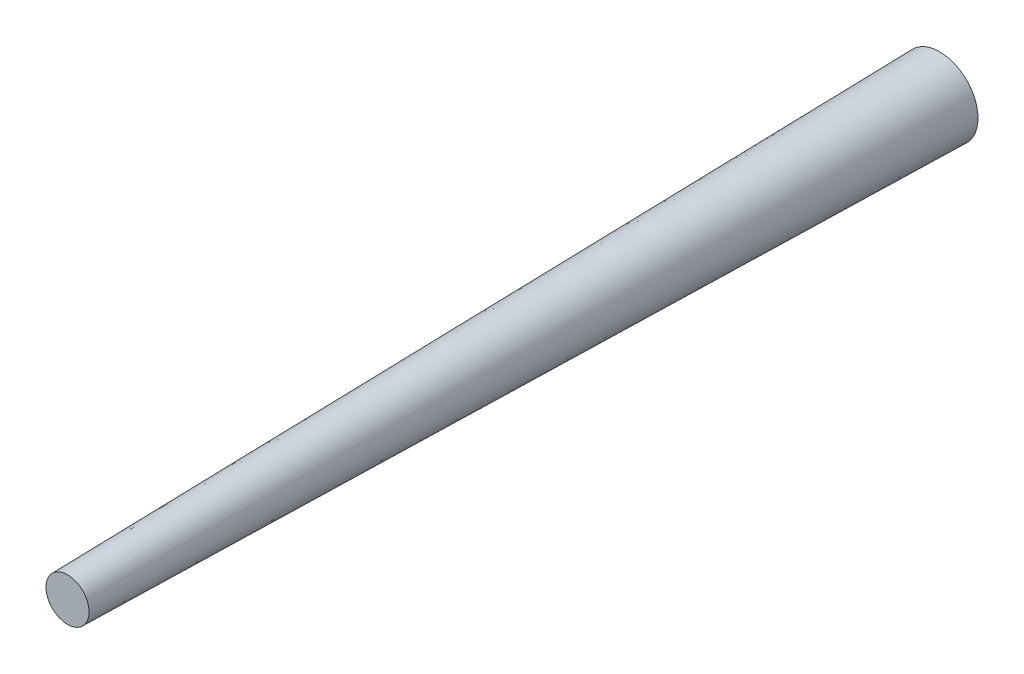
SolidWorks part; units mm, degrees
ref_plane "Front Plane" through (0, 0, 0) normal (0, 0, 1) x (1, 0, 0)
ref_plane "Top Plane" through (0, 0, 0) normal (0, 1, 0) x (1, 0, 0)
ref_plane "Right Plane" through (0, 0, 0) normal (1, 0, 0) x (0, 0, -1)
sketch "Sketch1" plane through (0, 0, 0) normal (0, 1, 0) x (1, 0, 0)
  line L0 (27, -409.6923) -> (0, -409.6923)
  line L1 (0, -409.6923) -> (0, -1024.6923)
  line L2 (0, -1024.6923) -> (15.1914, -1024.6923)
  line L3 (15.1914, -1024.6923) -> (27, -409.6923)
  line L4 (0, -409.6923) -> (0, -1024.6923) construction
revolve "Revolve1" add sketch "Sketch1" angle 360 about L4
